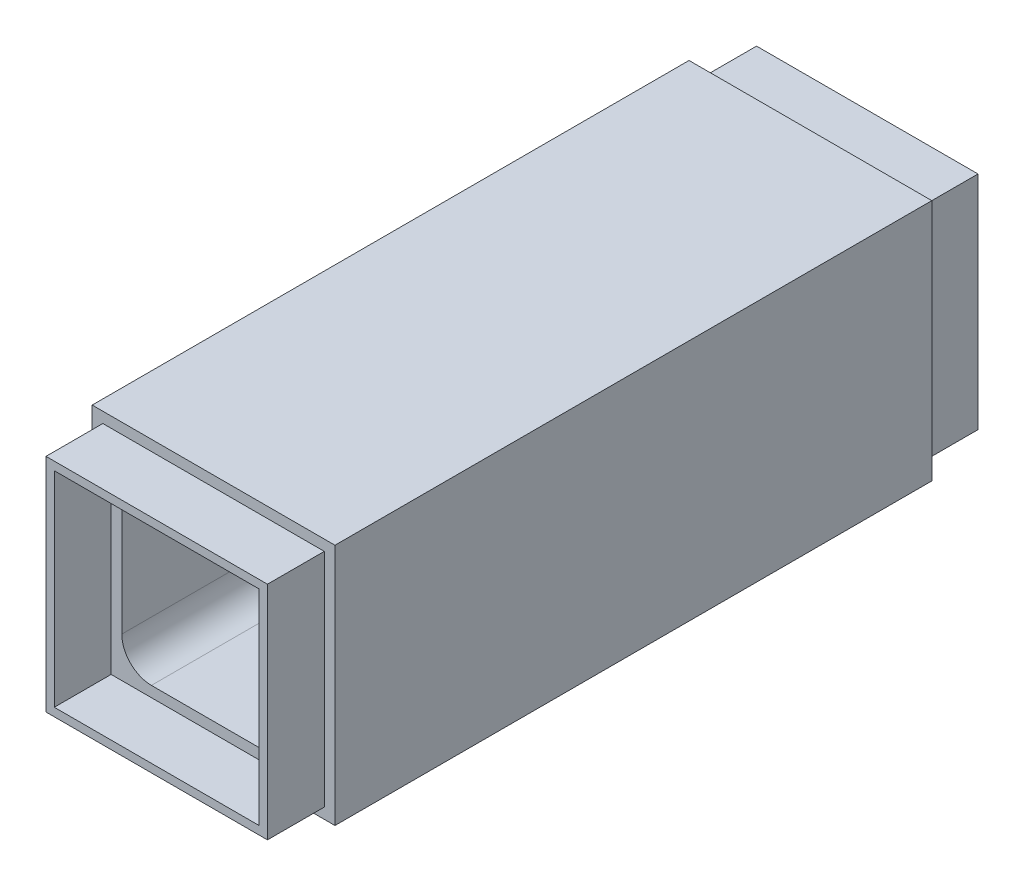
SolidWorks part; units mm, degrees
ref_plane "Front Plane" through (0, 0, 0) normal (0, 0, 1) x (1, 0, 0)
ref_plane "Top Plane" through (0, 0, 0) normal (0, 1, 0) x (1, 0, 0)
ref_plane "Right Plane" through (0, 0, 0) normal (1, 0, 0) x (0, 0, -1)
sketch "Sketch1" plane through (0, 0, 0) normal (0, 0, 1) x (1, 0, 0)
  line L1 (0, 0) -> (52.07, 0)
  line L2 (0, 0) -> (0, 52.07)
  line L3 (0, 52.07) -> (52.07, 52.07)
  line L4 (52.07, 0) -> (52.07, 52.07)
  dimension "D1" = 52.07
  dimension "D2" = 52.07
extrude "Boss-Extrude1" add sketch "Sketch1" against normal blind 152.4
sketch "Sketch2" plane through (0, 0, 0) normal (0, 0, 1) x (1, 0, 0)
  line L0 (0, 52.07) -> (0, 0) construction
  line L1 (6.35, 45.72) -> (45.72, 45.72)
  line L2 (6.35, 45.72) -> (6.35, 6.35)
  line L3 (6.35, 6.35) -> (45.72, 6.35)
  line L4 (45.72, 45.72) -> (45.72, 6.35)
  line L5 (0, 0) -> (52.07, 0) construction
  line L6 (52.07, 0) -> (52.07, 52.07) construction
  line L7 (52.07, 52.07) -> (0, 52.07) construction
  dimension "D1" = 6.35
  dimension "D2" = 6.35
  dimension "D3" = 6.35
  dimension "D4" = 6.35
extrude "Cut-Extrude1" cut sketch "Sketch2" against normal through all
sketch "Sketch3" plane through (0, 0, 0) normal (0, 0, 1) x (1, 0, 0)
  line L0 (0, 52.07) -> (0, 0) construction
  line L1 (2.286, 49.784) -> (49.784, 49.784)
  line L2 (2.286, 49.784) -> (2.286, 2.286)
  line L3 (2.286, 2.286) -> (49.784, 2.286)
  line L4 (49.784, 49.784) -> (49.784, 2.286)
  line L5 (52.07, 0) -> (52.07, 52.07) construction
  line L6 (0, 0) -> (52.07, 0) construction
  line L7 (52.07, 52.07) -> (0, 52.07) construction
  line L9 (4.064, 48.006) -> (48.006, 48.006)
  line L10 (4.064, 48.006) -> (4.064, 4.064)
  line L11 (4.064, 4.064) -> (48.006, 4.064)
  line L12 (48.006, 48.006) -> (48.006, 4.064)
  line M9 (45.72, 6.35) -> (6.35, 6.35)
  line M10 (6.35, 6.35) -> (6.35, 45.72)
  line M11 (6.35, 45.72) -> (45.72, 45.72)
  line M12 (45.72, 45.72) -> (45.72, 6.35)
  line M13 (0, 52.07) -> (0, 0)
  line M14 (0, 0) -> (52.07, 0)
  line M15 (52.07, 0) -> (52.07, 52.07)
  line M16 (52.07, 52.07) -> (0, 52.07)
  dimension "D1" = 2.286
  dimension "D2" = 2.286
  dimension "D3" = 2.286
  dimension "D4" = 2.286
  dimension "D5" = 1.778
  dimension "D6" = 1.778
  dimension "D7" = 1.778
  dimension "D8" = 1.778
extrude "Cut-Extrude2" cut sketch "Sketch3" against normal blind 12.192 contours L1 L4 L3 L2 M16 M13 M14 M15 | L12 L9 L10 L11 M12 M9 M10 M11
ref_plane "Plane1" through (0, 0, -76.2) normal (0, 0, -1) x (-1, 0, 0)
mirror "Mirror1" about plane through (0, 0, -76.2) normal (0, 0, -1) of "Cut-Extrude2"
fillet "Fillet1" radius 6.35 4 edges at (6.35, 45.72, -76.2) (45.72, 45.72, -76.2) (45.72, 6.35, -76.2) (6.35, 6.35, -76.2)
